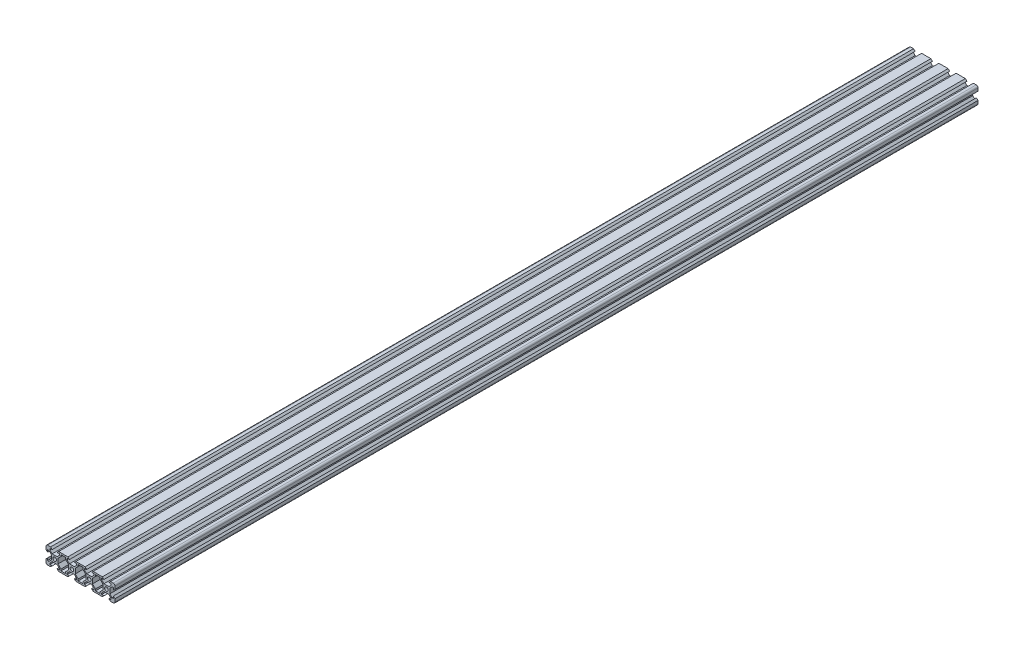
SolidWorks part; units mm, degrees
ref_plane "Front Plane" through (0, 0, 0) normal (0, 0, 1) x (1, 0, 0)
ref_plane "Top Plane" through (0, 0, 0) normal (0, 1, 0) x (1, 0, 0)
ref_plane "Right Plane" through (0, 0, 0) normal (1, 0, 0) x (0, 0, -1)
ref_plane "Plane1" through (0, 0, 0) normal (0, 0, -1) x (-1, 0, 0)
sketch "Sketch1" plane through (0, 0, 0) normal (0, 0, -1) x (-1, 0, 0)
  line L0 (17.3007, -6.24) -> (13.9007, -2.84)
  line L1 (13.9007, -2.84) -> (13.9007, 2.84)
  line L2 (13.9007, 2.84) -> (17.3007, 6.24)
  line L3 (17.3007, 6.24) -> (17.3007, 8.2)
  line L4 (17.3007, 8.2) -> (22.6993, 8.2)
  line L5 (22.6993, 8.2) -> (22.6993, 6.24)
  line L6 (22.6993, 6.24) -> (26.0993, 2.84)
  line L7 (26.0993, 2.84) -> (26.0993, -2.84)
  line L8 (26.0993, -2.84) -> (22.6993, -6.24)
  line L9 (22.6993, -6.24) -> (22.6993, -8.2)
  line L10 (22.6993, -8.2) -> (17.3007, -8.2)
  line L11 (17.3007, -8.2) -> (17.3007, -6.24)
  line L12 (2.6993, 6.24) -> (6.0993, 2.84)
  line L13 (6.0993, 2.84) -> (6.0993, -2.84)
  line L14 (6.0993, -2.84) -> (2.6993, -6.24)
  line L15 (2.6993, -6.24) -> (2.6993, -8.2)
  line L16 (2.6993, -8.2) -> (-2.6993, -8.2)
  line L17 (-2.6993, -8.2) -> (-2.6993, -6.24)
  line L18 (-2.6993, -6.24) -> (-6.0993, -2.84)
  line L19 (-6.0993, -2.84) -> (-6.0993, 2.84)
  line L20 (-6.0993, 2.84) -> (-2.6993, 6.24)
  line L21 (-2.6993, 6.24) -> (-2.6993, 8.2)
  line L22 (-2.6993, 8.2) -> (2.6993, 8.2)
  line L23 (2.6993, 8.2) -> (2.6993, 6.24)
  line L24 (-13.9007, -2.84) -> (-17.3007, -6.24)
  line L25 (-17.3007, -6.24) -> (-17.3007, -8.2)
  line L26 (-17.3007, -8.2) -> (-22.6993, -8.2)
  line L27 (-22.6993, -8.2) -> (-22.6993, -6.24)
  line L28 (-22.6993, -6.24) -> (-26.0993, -2.84)
  line L29 (-26.0993, -2.84) -> (-26.0993, 2.84)
  line L30 (-26.0993, 2.84) -> (-22.6993, 6.24)
  line L31 (-22.6993, 6.24) -> (-22.6993, 8.2)
  line L32 (-22.6993, 8.2) -> (-17.3007, 8.2)
  line L33 (-17.3007, 8.2) -> (-17.3007, 6.24)
  line L34 (-17.3007, 6.24) -> (-13.9007, 2.84)
  line L35 (-13.9007, 2.84) -> (-13.9007, -2.84)
  line L36 (15.4993, -8.2) -> (12.84, -8.2)
  line L37 (12.84, -8.2) -> (14.64, -10)
  line L38 (14.64, -10) -> (25.36, -10)
  line L39 (25.36, -10) -> (27.16, -8.2)
  line L40 (27.16, -8.2) -> (24.5007, -8.2)
  line L41 (24.5007, -8.2) -> (24.5007, -6.56)
  line L42 (24.5007, -6.56) -> (27.16, -3.9007)
  line L43 (27.16, -3.9007) -> (32.84, -3.9007)
  line L44 (32.84, -3.9007) -> (35.4993, -6.56)
  line L45 (35.4993, -6.56) -> (35.4993, -8.2)
  line L46 (35.4993, -8.2) -> (32.84, -8.2)
  line L47 (32.84, -8.2) -> (34.64, -10)
  line L48 (34.64, -10) -> (38, -10)
  line L49 (40, -8) -> (40, -4.64)
  line L50 (40, -4.64) -> (38.2, -2.84)
  line L51 (38.2, -2.84) -> (38.2, -5.4993)
  line L52 (38.2, -5.4993) -> (36.56, -5.4993)
  line L53 (36.56, -5.4993) -> (33.9007, -2.84)
  line L54 (33.9007, -2.84) -> (33.9007, 2.84)
  line L55 (33.9007, 2.84) -> (36.56, 5.4993)
  line L56 (36.56, 5.4993) -> (38.2, 5.4993)
  line L57 (38.2, 5.4993) -> (38.2, 2.84)
  line L58 (38.2, 2.84) -> (40, 4.64)
  line L59 (40, 4.64) -> (40, 8)
  line L60 (38, 10) -> (34.64, 10)
  line L61 (34.64, 10) -> (32.84, 8.2)
  line L62 (32.84, 8.2) -> (35.4993, 8.2)
  line L63 (35.4993, 8.2) -> (35.4993, 6.56)
  line L64 (35.4993, 6.56) -> (32.84, 3.9007)
  line L65 (32.84, 3.9007) -> (27.16, 3.9007)
  line L66 (27.16, 3.9007) -> (24.5007, 6.56)
  line L67 (24.5007, 6.56) -> (24.5007, 8.2)
  line L68 (24.5007, 8.2) -> (27.16, 8.2)
  line L69 (27.16, 8.2) -> (25.36, 10)
  line L70 (25.36, 10) -> (14.64, 10)
  line L71 (14.64, 10) -> (12.84, 8.2)
  line L72 (12.84, 8.2) -> (15.4993, 8.2)
  line L73 (15.4993, 8.2) -> (15.4993, 6.56)
  line L74 (15.4993, 6.56) -> (12.84, 3.9007)
  line L75 (12.84, 3.9007) -> (7.16, 3.9007)
  line L76 (7.16, 3.9007) -> (4.5007, 6.56)
  line L77 (4.5007, 6.56) -> (4.5007, 8.2)
  line L78 (4.5007, 8.2) -> (7.16, 8.2)
  line L79 (7.16, 8.2) -> (5.36, 10)
  line L80 (5.36, 10) -> (-5.36, 10)
  line L81 (-5.36, 10) -> (-7.16, 8.2)
  line L82 (-7.16, 8.2) -> (-4.5007, 8.2)
  line L83 (-4.5007, 8.2) -> (-4.5007, 6.56)
  line L84 (-4.5007, 6.56) -> (-7.16, 3.9007)
  line L85 (-7.16, 3.9007) -> (-12.84, 3.9007)
  line L86 (-12.84, 3.9007) -> (-15.4993, 6.56)
  line L87 (-15.4993, 6.56) -> (-15.4993, 8.2)
  line L88 (-15.4993, 8.2) -> (-12.84, 8.2)
  line L89 (-12.84, 8.2) -> (-14.64, 10)
  line L90 (-14.64, 10) -> (-25.36, 10)
  line L91 (-25.36, 10) -> (-27.16, 8.2)
  line L92 (-27.16, 8.2) -> (-24.5007, 8.2)
  line L93 (-24.5007, 8.2) -> (-24.5007, 6.56)
  line L94 (-24.5007, 6.56) -> (-27.16, 3.9007)
  line L95 (-27.16, 3.9007) -> (-32.84, 3.9007)
  line L96 (-32.84, 3.9007) -> (-35.4993, 6.56)
  line L97 (-35.4993, 6.56) -> (-35.4993, 8.2)
  line L98 (-35.4993, 8.2) -> (-32.84, 8.2)
  line L99 (-32.84, 8.2) -> (-34.64, 10)
  line L100 (-34.64, 10) -> (-38, 10)
  line L101 (-40, 8) -> (-40, 4.64)
  line L102 (-40, 4.64) -> (-38.2, 2.84)
  line L103 (-38.2, 2.84) -> (-38.2, 5.4993)
  line L104 (-38.2, 5.4993) -> (-36.56, 5.4993)
  line L105 (-36.56, 5.4993) -> (-33.9007, 2.84)
  line L106 (-33.9007, 2.84) -> (-33.9007, -2.84)
  line L107 (-33.9007, -2.84) -> (-36.56, -5.4993)
  line L108 (-36.56, -5.4993) -> (-38.2, -5.4993)
  line L109 (-38.2, -5.4993) -> (-38.2, -2.84)
  line L110 (-38.2, -2.84) -> (-40, -4.64)
  line L111 (-40, -4.64) -> (-40, -8)
  line L112 (-38, -10) -> (-34.64, -10)
  line L113 (-34.64, -10) -> (-32.84, -8.2)
  line L114 (-32.84, -8.2) -> (-35.4993, -8.2)
  line L115 (-35.4993, -8.2) -> (-35.4993, -6.56)
  line L116 (-35.4993, -6.56) -> (-32.84, -3.9007)
  line L117 (-32.84, -3.9007) -> (-27.16, -3.9007)
  line L118 (-27.16, -3.9007) -> (-24.5007, -6.56)
  line L119 (-24.5007, -6.56) -> (-24.5007, -8.2)
  line L120 (-24.5007, -8.2) -> (-27.16, -8.2)
  line L121 (-27.16, -8.2) -> (-25.36, -10)
  line L122 (-25.36, -10) -> (-14.64, -10)
  line L123 (-14.64, -10) -> (-12.84, -8.2)
  line L124 (-12.84, -8.2) -> (-15.4993, -8.2)
  line L125 (-15.4993, -8.2) -> (-15.4993, -6.56)
  line L126 (-15.4993, -6.56) -> (-12.84, -3.9007)
  line L127 (-12.84, -3.9007) -> (-7.16, -3.9007)
  line L128 (-7.16, -3.9007) -> (-4.5007, -6.56)
  line L129 (-4.5007, -6.56) -> (-4.5007, -8.2)
  line L130 (-4.5007, -8.2) -> (-7.16, -8.2)
  line L131 (-7.16, -8.2) -> (-5.36, -10)
  line L132 (-5.36, -10) -> (5.36, -10)
  line L133 (5.36, -10) -> (7.16, -8.2)
  line L134 (7.16, -8.2) -> (4.5007, -8.2)
  line L135 (4.5007, -8.2) -> (4.5007, -6.56)
  line L136 (4.5007, -6.56) -> (7.16, -3.9007)
  line L137 (7.16, -3.9007) -> (12.84, -3.9007)
  line L138 (12.84, -3.9007) -> (15.4993, -6.56)
  line L139 (15.4993, -6.56) -> (15.4993, -8.2)
  circle A0 centre (10, 0) radius 2.1
  circle A1 centre (30, 0) radius 2.1
  circle A2 centre (-10, 0) radius 2.1
  circle A3 centre (-30, 0) radius 2.1
  arc A4 (38, -10) -> (40, -8) centre (38, -8) ccw
  arc A5 (40, 8) -> (38, 10) centre (38, 8) ccw
  arc A6 (-38, 10) -> (-40, 8) centre (-38, 8) ccw
  arc A7 (-40, -8) -> (-38, -10) centre (-38, -8) ccw
extrude "Boss-Extrude1" add sketch "Sketch1" against normal blind 1000
